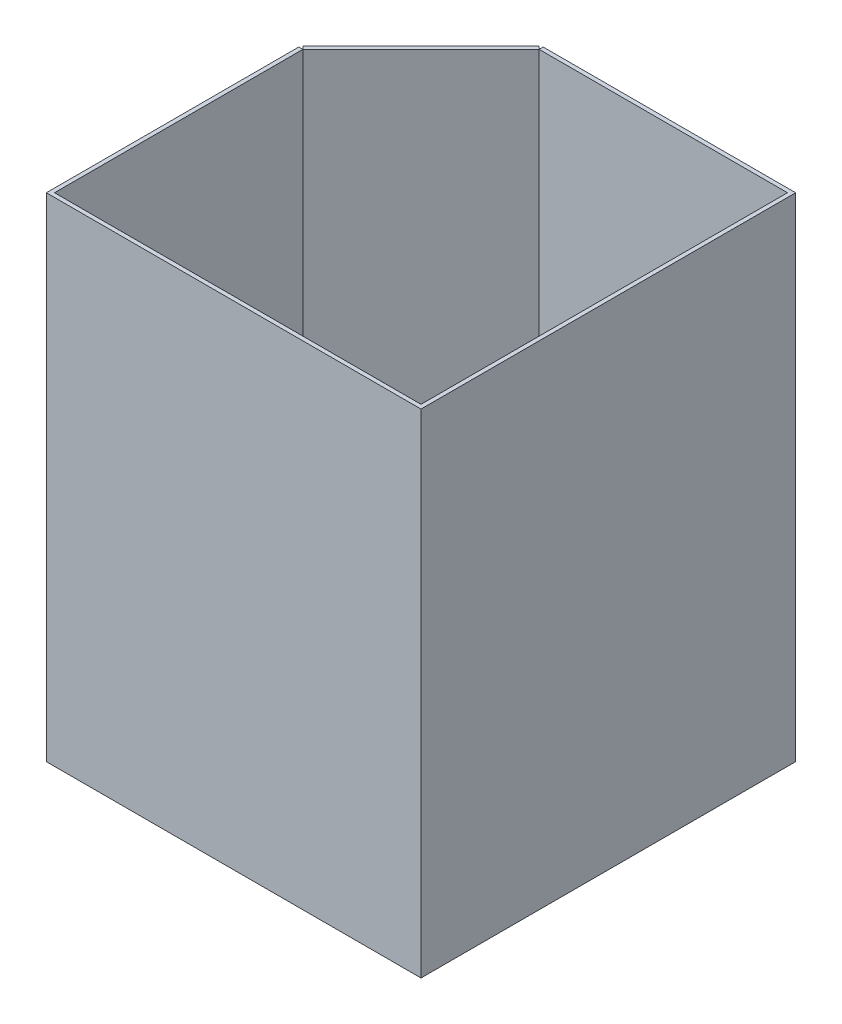
SolidWorks part; units mm, degrees
ref_plane "Front Plane" through (0, 0, 0) normal (0, 0, 1) x (1, 0, 0)
ref_plane "Top Plane" through (0, 0, 0) normal (0, 1, 0) x (1, 0, 0)
ref_plane "Right Plane" through (0, 0, 0) normal (1, 0, 0) x (0, 0, -1)
sketch "Sketch1" plane through (0, 0, 0) normal (0, 1, 0) x (1, 0, 0)
  line L0 (-41.7678, 114.2678) -> (-114.2678, 41.7678)
  line L1 (-115, -115) -> (115, -115)
  line L2 (-115, -115) -> (-115, 40)
  line L3 (-40, 115) -> (115, 115)
  line L4 (115, -115) -> (115, 115)
  line L5 (-115, -115) -> (115, 115) construction
  line L6 (-115, 40) -> (-112.8776, 40)
  line L7 (-112.5, -112.5) -> (112.5, -112.5)
  line L8 (-112.5, -112.5) -> (-112.5, 40)
  line L9 (-40, 112.5) -> (112.5, 112.5)
  line L10 (112.5, -112.5) -> (112.5, 112.5)
  line L11 (-112.5, -112.5) -> (112.5, 112.5) construction
  line L12 (-78.0178, 78.0178) -> (112.5, -112.5) construction
  line L13 (-78.0178, 78.0178) -> (115, -115) construction
  line L14 (-40, 115) -> (-40, 113.0784)
  line L15 (-112.771, 40.271) -> (-114.2678, 41.7678)
  line L16 (-40.3445, 112.8445) -> (-41.7678, 114.2678)
  line L17 (-40, 112.5) -> (-112.5, 40)
  line L18 (-40.3445, 112.8445) -> (-40, 113.0784)
  line L19 (-112.771, 40.271) -> (-112.8776, 40)
  point P0 (0, 0)
  point P5 (0, 0)
  point P20 (0, 0)
  dimension "D1" = 2.5
  dimension "D2" = 2.5
extrude "Boss-Extrude1" add sketch "Sketch1" along normal blind 300
sketch "Sketch2" plane through (0, 0, 0) normal (0, -1, 0) x (1, 0, 0)
  line L15 (115, -115) -> (115, 115)
  line L16 (115, 115) -> (-115, 115)
  line L17 (-115, 115) -> (-115, -40)
  line L18 (-115, -40) -> (-112.8776, -40)
  line L19 (-112.8776, -40) -> (-112.771, -40.271)
  line L20 (-112.771, -40.271) -> (-114.2678, -41.7678)
  line L21 (-114.2678, -41.7678) -> (-41.7678, -114.2678)
  line L22 (-41.7678, -114.2678) -> (-40.3445, -112.8445)
  line L23 (-40.3445, -112.8445) -> (-40, -113.0784)
  line L24 (-40, -113.0784) -> (-40, -115)
  line L25 (-40, -115) -> (115, -115)
  line L26 (115, -115) -> (115, 115)
  line L27 (115, 115) -> (-115, 115)
  line L28 (-115, 115) -> (-115, -40)
  line L29 (-115, -40) -> (-112.8776, -40)
  line L30 (-112.8776, -40) -> (-112.771, -40.271)
  line L31 (-112.771, -40.271) -> (-114.2678, -41.7678)
  line L32 (-114.2678, -41.7678) -> (-41.7678, -114.2678)
  line L33 (-41.7678, -114.2678) -> (-40.3445, -112.8445)
  line L34 (-40.3445, -112.8445) -> (-40, -113.0784)
  line L35 (-40, -113.0784) -> (-40, -115)
  line L36 (-40, -115) -> (115, -115)
  dimension "D1" = 0
extrude "Boss-Extrude2" add sketch "Sketch2" along normal blind 2.5
